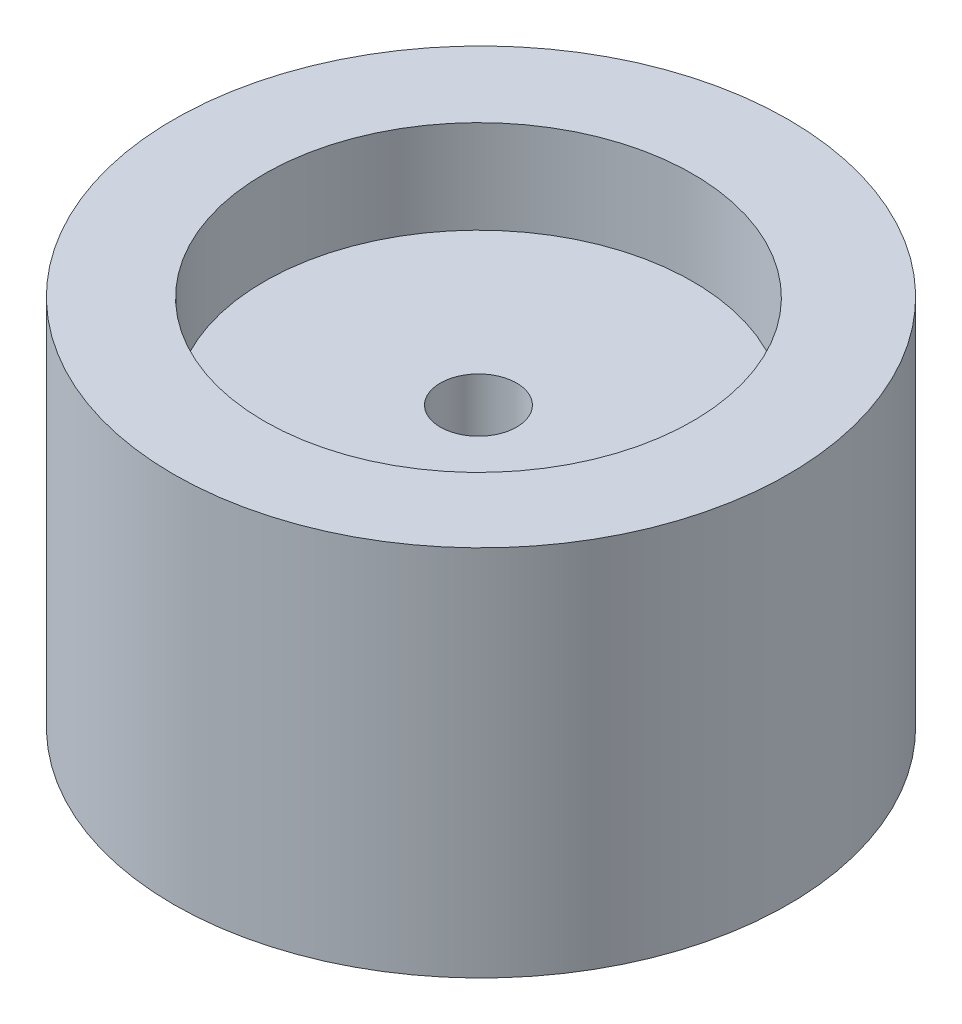
SolidWorks part; units mm, degrees
ref_plane "Front Plane" through (0, 0, 0) normal (0, 0, 1) x (1, 0, 0)
ref_plane "Top Plane" through (0, 0, 0) normal (0, 1, 0) x (1, 0, 0)
ref_plane "Right Plane" through (0, 0, 0) normal (1, 0, 0) x (0, 0, -1)
sketch "Sketch1" plane through (0, 0, 0) normal (0, 1, 0) x (1, 0, 0)
  circle A0 centre (-11.0733, 20.9976) radius 16.5
extrude "Boss-Extrude1" add sketch "Sketch1" along normal blind 20
sketch "Sketch2" plane through (0, 20, 0) normal (0, 1, 0) x (1, 0, 0)
  circle A0 centre (-11.1121, 20.9007) radius 2.05
extrude "Cut-Extrude1" cut sketch "Sketch2" against normal through all
sketch "Sketch9" plane through (0, 20, 0) normal (0, 1, 0) x (1, 0, 0)
  circle A0 centre (-11.1121, 20.9007) radius 11.5
extrude "Cut-Extrude2" cut sketch "Sketch9" against normal blind 5 contours A0
